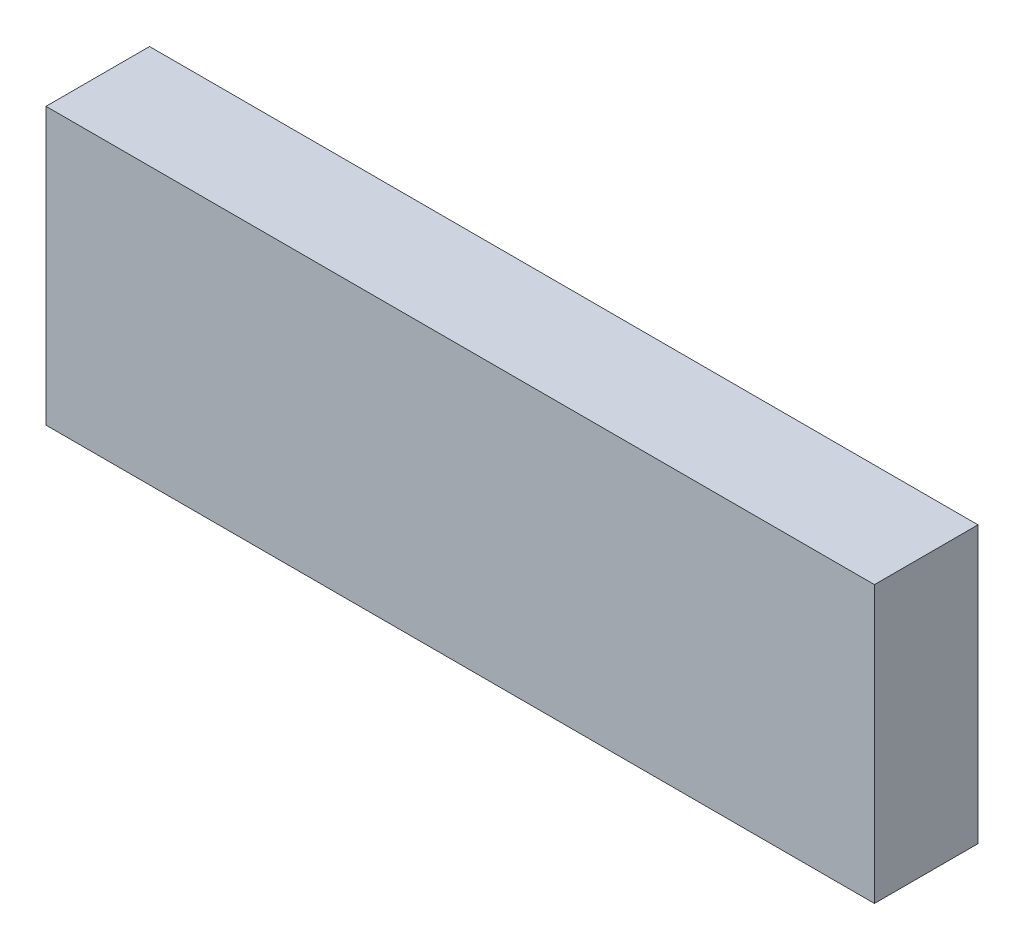
SolidWorks part; units mm, degrees
material "ABS"
ref_plane "Front Plane" through (0, 0, 0) normal (0, 0, 1) x (1, 0, 0)
ref_plane "Top Plane" through (0, 0, 0) normal (0, 1, 0) x (1, 0, 0)
ref_plane "Right Plane" through (0, 0, 0) normal (1, 0, 0) x (0, 0, -1)
sketch "Sketch1" plane through (0, 0, 0) normal (0, 0, 1) x (1, 0, 0)
  line L1 (0, 0) -> (1200, 0)
  line L2 (0, 0) -> (0, 400)
  line L3 (0, 400) -> (1200, 400)
  line L4 (1200, 0) -> (1200, 400)
  dimension "D1" = 1200
  dimension "D2" = 400
extrude "Boss-Extrude1" add sketch "Sketch1" along normal blind 150
